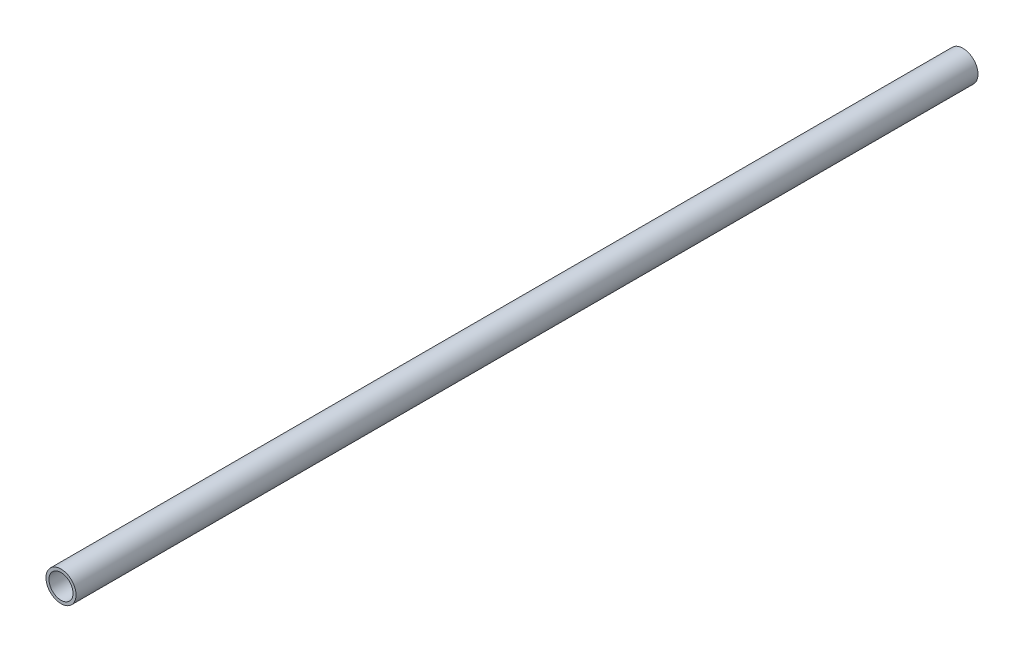
SolidWorks part; units mm, degrees
material "Thornel VCB-20 ｶｰﾎﾞﾝ ｸﾛｽ"
ref_plane "正面" through (0, 0, 0) normal (0, 0, 1) x (1, 0, 0)
ref_plane "平面" through (0, 0, 0) normal (0, 1, 0) x (1, 0, 0)
ref_plane "右側面" through (0, 0, 0) normal (1, 0, 0) x (0, 0, -1)
sketch "ｽｹｯﾁ1" plane through (0, 0, 0) normal (0, 0, 1) x (1, 0, 0)
  circle A0 centre (0, 0) radius 5
  circle A1 centre (0, 0) radius 4
  dimension "D1" = 10
  dimension "D2" = 8
extrude "ﾎﾞｽ - 押し出し1" add sketch "ｽｹｯﾁ1" along normal blind 300
sketch "ｽｹｯﾁ2" plane through (0, 0, 0) normal (0, 1, 0) x (1, 0, 0)
  line L0 (0, 0) -> (0, -300) construction
  line L1 (-4, -300) -> (4, -300) construction
